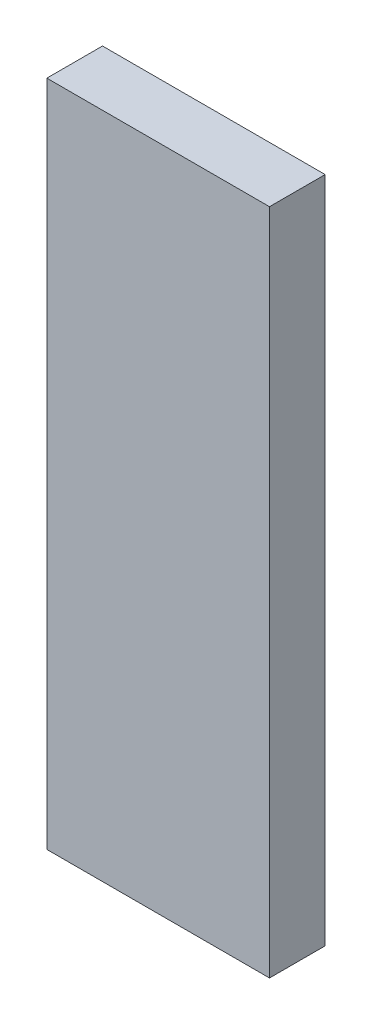
SolidWorks part; units mm, degrees
ref_plane "Front Plane" through (0, 0, 0) normal (0, 0, 1) x (1, 0, 0)
ref_plane "Top Plane" through (0, 0, 0) normal (0, 1, 0) x (1, 0, 0)
ref_plane "Right Plane" through (0, 0, 0) normal (1, 0, 0) x (0, 0, -1)
sketch "Sketch1" plane through (0, 0, 0) normal (0, 1, 0) x (1, 0, 0)
  line L1 (0, 0) -> (50.8, 0)
  line L2 (0, 0) -> (0, 12.7)
  line L3 (0, 12.7) -> (50.8, 12.7)
  line L4 (50.8, 0) -> (50.8, 12.7)
  dimension "D1" = 50.8
  dimension "D2" = 12.7
extrude "Boss-Extrude1" add sketch "Sketch1" along normal blind 152.4
